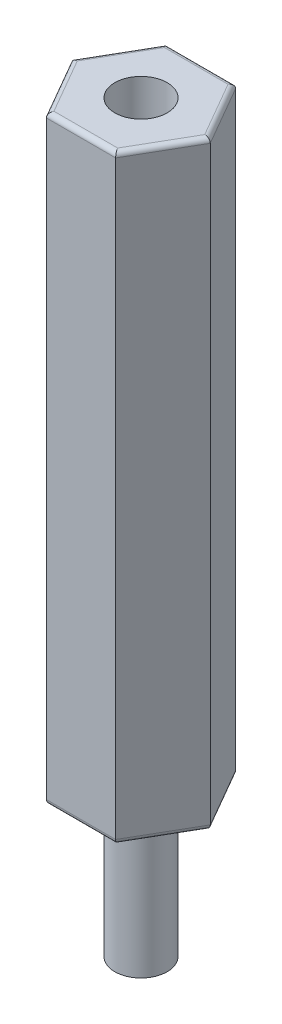
SolidWorks part; units mm, degrees
material "201.0-T43 Molde de fundição com isolamento (SS)"
ref_plane "Plano frontal" through (0, 0, 0) normal (0, 0, 1) x (1, 0, 0)
ref_plane "Plano superior" through (0, 0, 0) normal (0, 1, 0) x (1, 0, 0)
ref_plane "Plano direito" through (0, 0, 0) normal (1, 0, 0) x (0, 0, -1)
sketch "Esboço1" plane through (0, 0, 0) normal (0, 1, 0) x (1, 0, 0)
  line L1 (2.8868, 0) -> (1.4434, 2.5)
  line L2 (1.4434, 2.5) -> (-1.4434, 2.5)
  line L3 (-1.4434, 2.5) -> (-2.8868, 0)
  line L4 (-2.8868, 0) -> (-1.4434, -2.5)
  line L5 (-1.4434, -2.5) -> (1.4434, -2.5)
  line L6 (1.4434, -2.5) -> (2.8868, 0)
  circle A0 centre (0, 0) radius 2.5 construction
  dimension "D1" = 5
extrude "Ressalto-extrusão1" add sketch "Esboço1" along normal blind 25
fillet "Filete1" radius 0.2 12 edges at (0, 25, -2.5) (-2.1651, 25, -1.25) (-2.1651, 25, 1.25) (0, 25, 2.5) (2.1651, 25, 1.25) (2.1651, 25, -1.25) (0, 0, 2.5) (-2.1651, 0, 1.25) (-2.1651, 0, -1.25) (0, 0, -2.5) (2.1651, 0, -1.25) (2.1651, 0, 1.25)
sketch "Esboço2" plane through (0, 0, 0) normal (0, -1, 0) x (1, 0, 0)
  circle A0 centre (0, 0) radius 1.0922
  dimension "D1" = 2.1844
extrude "Ressalto-extrusão2" add sketch "Esboço2" along normal blind 6
sketch "Esboço3" plane through (0, 25, 0) normal (0, 1, 0) x (1, 0, 0)
  circle A0 centre (0, 0) radius 1.0922
extrude "Corte-extrusão1" cut sketch "Esboço3" against normal blind 4.76
